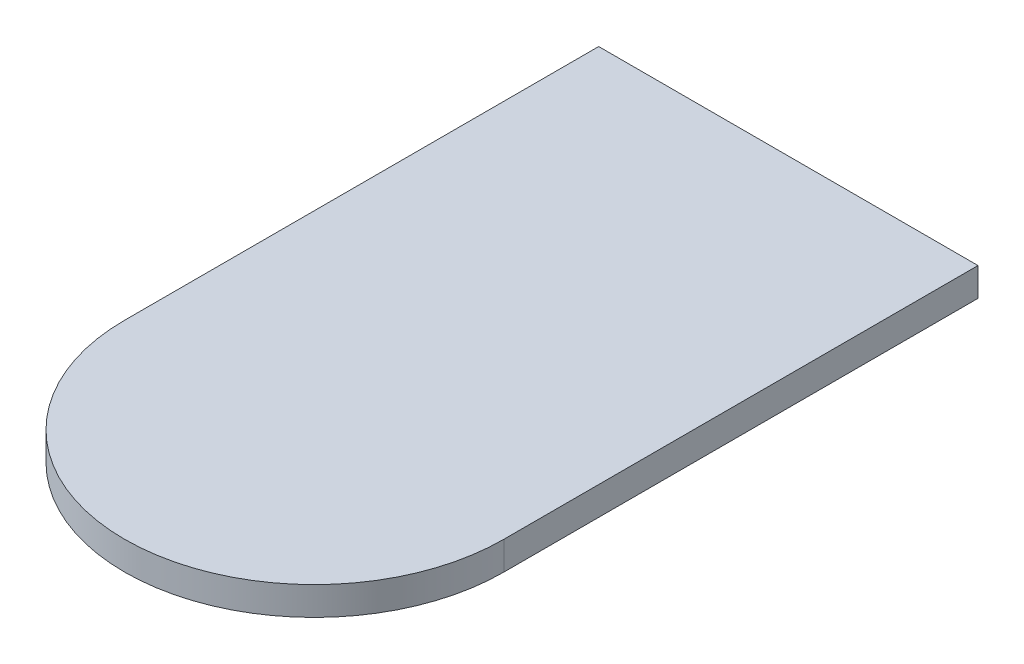
SolidWorks part; units mm, degrees
ref_plane "前基準面" through (0, 0, 0) normal (0, 0, 1) x (1, 0, 0)
ref_plane "上基準面" through (0, 0, 0) normal (0, 1, 0) x (1, 0, 0)
ref_plane "右基準面" through (0, 0, 0) normal (1, 0, 0) x (0, 0, -1)
sketch "草圖1" plane through (0, 0, 0) normal (0, 1, 0) x (1, 0, 0)
  line L0 (8, 0) -> (8, 20)
  line L1 (-8, 0) -> (-8, 20)
  line L2 (-8, 20) -> (8, 20)
  arc A0 (-8, 0) -> (8, 0) centre (0, 0) ccw
  dimension "D1" = 16
  dimension "D2" = 20
  dimension "D3" = 20
extrude "填料-伸長1" add sketch "草圖1" along normal blind 1.2
